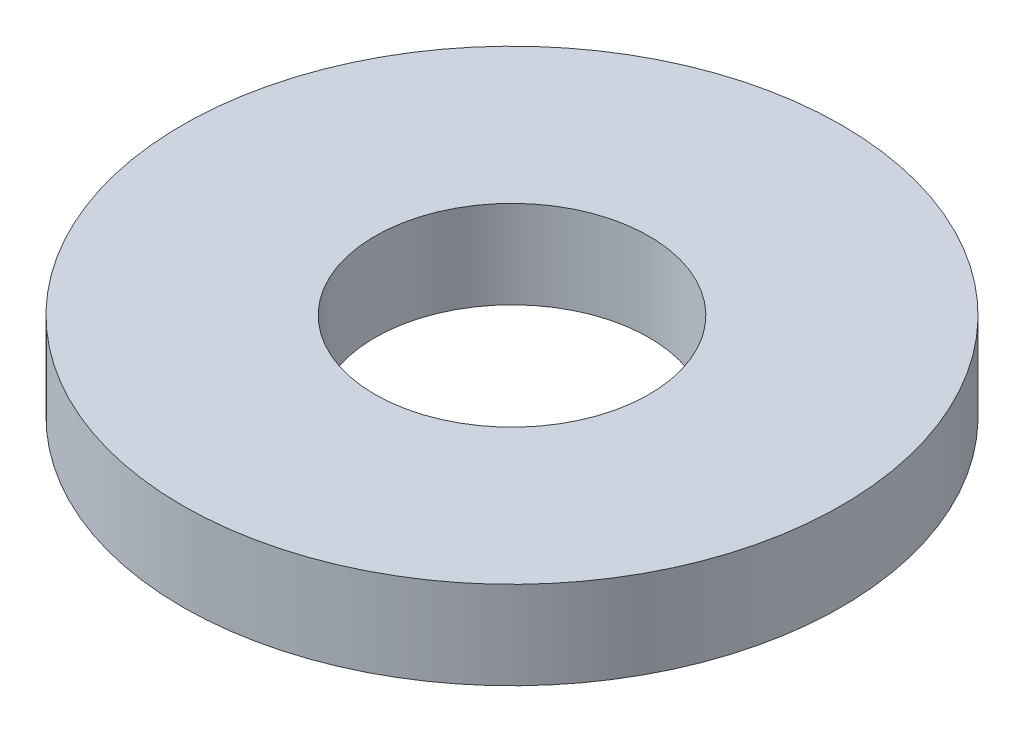
SolidWorks part; units mm, degrees
ref_plane "Front Plane" through (0, 0, 0) normal (0, 0, 1) x (1, 0, 0)
ref_plane "Top Plane" through (0, 0, 0) normal (0, 1, 0) x (1, 0, 0)
ref_plane "Right Plane" through (0, 0, 0) normal (1, 0, 0) x (0, 0, -1)
sketch "Sketch1" plane through (0, 0, 0) normal (0, 1, 0) x (1, 0, 0)
  circle A0 centre (0, 0) radius 2.3813
  dimension "OD" = 4.7625
extrude "Boss-Extrude1" add sketch "Sketch1" along normal blind 0.635
sketch "Sketch5" plane through (0, 0.635, 0) normal (0, 1, 0) x (-1, 0, 0)
  circle A0 centre (0, 0) radius 0.9906
  dimension "ID" = 1.9812
extrude "Cut-Extrude1" cut sketch "Sketch5" against normal through all
